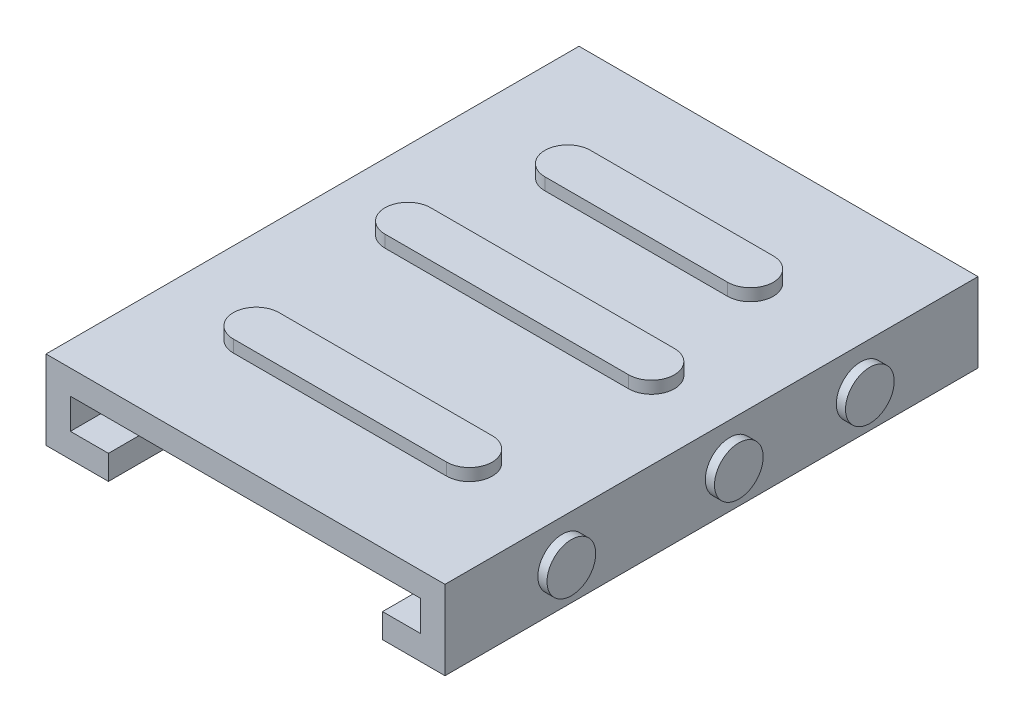
SolidWorks part; units mm, degrees
ref_plane "Front Plane" through (0, 0, 0) normal (0, 0, 1) x (1, 0, 0)
ref_plane "Top Plane" through (0, 0, 0) normal (0, 1, 0) x (1, 0, 0)
ref_plane "Right Plane" through (0, 0, 0) normal (1, 0, 0) x (0, 0, -1)
sketch "Sketch1" plane through (0, 0, 0) normal (0, 0, 1) x (1, 0, 0)
  line L0 (-59.6407, 7.2612) -> (-41.6407, 7.2612)
  line L30 (-62.1407, 7.2612) -> (-39.1407, 7.2612)
  line L34 (-62.1407, 7.2612) -> (-62.1407, 9.2612)
  line L36 (-62.1407, 9.2612) -> (-39.1407, 9.2612)
  line L37 (-39.1407, 7.2612) -> (-39.1407, 9.2612)
  line L38 (-50.6407, 9.2612) -> (-50.6407, 4.8275) construction
  line L39 (-59.6407, 7.2612) -> (-59.6407, 5.6612)
  line L40 (-59.6407, 5.6612) -> (-63.7407, 5.6612)
  line L41 (-63.7407, 5.6612) -> (-63.7407, 10.8612)
  line L42 (-63.7407, 10.8612) -> (-37.5407, 10.8612)
  line L43 (-37.5407, 10.8612) -> (-37.5407, 5.6612)
  line L44 (-37.5407, 5.6612) -> (-41.6407, 5.6612)
  line L45 (-41.6407, 5.6612) -> (-41.6407, 7.2612)
  dimension "D1" = 2
  dimension "D2" = 2.5
  dimension "D3" = 2.5
  dimension "D4" = 1.6
  dimension "D5" = 1.6
  dimension "D6" = 1.6
  dimension "D7" = 1.6
extrude "Boss-Extrude1" add sketch "Sketch1" along normal blind 35 contours L45 L44 L43 L42 L41 L40 L39 L30 L34 L36 L37
sketch "Sketch2" plane through (0, 10.8612, 0) normal (0, 1, 0) x (1, 0, 0)
  line L0 (-50.6407, 0) -> (-50.6407, -35) construction
  line L1 (-63.7407, 0) -> (-37.5407, 0) construction
  line L2 (-63.7407, -35) -> (-37.5407, -35) construction
  line L3 (-58.6263, -16.3536) -> (-42.6263, -16.3536) construction
  line L4 (-58.6263, -14.8536) -> (-42.6263, -14.8536)
  line L5 (-58.6263, -17.8536) -> (-42.6263, -17.8536)
  line L6 (-56.6407, -7.843) -> (-44.6407, -7.843) construction
  line L7 (-56.6407, -6.343) -> (-44.6407, -6.343)
  line L8 (-56.6407, -9.343) -> (-44.6407, -9.343)
  line L9 (-57.6407, -27.2963) -> (-43.6407, -27.2963) construction
  line L10 (-57.6407, -25.7963) -> (-43.6407, -25.7963)
  line L11 (-57.6407, -28.7963) -> (-43.6407, -28.7963)
  arc A0 (-58.6263, -14.8536) -> (-58.6263, -17.8536) centre (-58.6263, -16.3536) ccw
  arc A1 (-42.6263, -17.8536) -> (-42.6263, -14.8536) centre (-42.6263, -16.3536) ccw
  arc A2 (-56.6407, -6.343) -> (-56.6407, -9.343) centre (-56.6407, -7.843) ccw
  arc A3 (-44.6407, -9.343) -> (-44.6407, -6.343) centre (-44.6407, -7.843) ccw
  arc A4 (-57.6407, -25.7963) -> (-57.6407, -28.7963) centre (-57.6407, -27.2963) ccw
  arc A5 (-43.6407, -28.7963) -> (-43.6407, -25.7963) centre (-43.6407, -27.2963) ccw
  point P8 (-50.6263, -16.3536)
  point P13 (-50.6407, -7.843)
  point P20 (-50.6407, -27.2963)
  point P27 (0, 0)
  point P28 (0, 0)
extrude "Boss-Extrude2" add sketch "Sketch2" along normal blind 0.8 contours L8 A3 L7 A2 | L5 A1 L4 A0 | L11 A5 L10 A4
sketch "Sketch3" plane through (-63.7407, 0, 0) normal (-1, 0, 0) x (0, 0, 1)
  line L0 (0, 8.2612) -> (35, 8.2612) construction
  line L1 (0, 5.6612) -> (0, 10.8612) construction
  line L2 (35, 5.6612) -> (35, 10.8612) construction
  circle A0 centre (7.5265, 8.2612) radius 1.5
  circle A1 centre (16.4955, 8.2612) radius 1.5
  circle A2 centre (27.2583, 8.2612) radius 1.5
extrude "Boss-Extrude3" add sketch "Sketch3" along normal blind 0.6
sketch "Sketch5" plane through (-37.5407, 0, 0) normal (1, 0, 0) x (0, 0, -1)
  line L0 (-35, 10.8612) -> (-35, 5.6612) construction
  line L1 (0, 8.2612) -> (-35, 8.2612)
  line L2 (0, 10.8612) -> (0, 5.6612) construction
  circle A0 centre (-27.3017, 8.2612) radius 1.6
  circle A1 centre (-16.3052, 8.2612) radius 1.6
  circle A2 centre (-7.7015, 8.2612) radius 1.6
extrude "Boss-Extrude4" add sketch "Sketch5" along normal blind 0.6 contours A2 | A1 | A0
sketch "Sketch6" plane through (0, 5.6612, 0) normal (0, -1, 0) x (1, 0, 0)
  line L0 (-40.3801, 24.2088) -> (-38.3837, 24.2088)
  line L1 (-62.7119, 24.557) -> (-60.7155, 24.557)
  line L2 (-62.7119, 24.557) -> (-62.7119, 23.2106)
  line L3 (-62.7119, 23.2106) -> (-60.7155, 23.2106)
  line L4 (-60.7155, 24.557) -> (-60.7155, 23.2106)
  line L5 (-62.7119, 19.6821) -> (-60.7155, 19.6821)
  line L6 (-62.7119, 19.6821) -> (-62.7119, 18.3357)
  line L7 (-62.7119, 18.3357) -> (-60.7155, 18.3357)
  line L8 (-60.7155, 19.6821) -> (-60.7155, 18.3357)
  line L9 (-62.7119, 14.2501) -> (-60.7155, 14.2501)
  line L10 (-62.7119, 14.2501) -> (-62.7119, 12.9036)
  line L11 (-62.7119, 12.9036) -> (-60.7155, 12.9036)
  line L12 (-60.7155, 14.2501) -> (-60.7155, 12.9036)
  line L13 (-62.7119, 10.2573) -> (-60.6691, 10.2573)
  line L14 (-62.7119, 10.2573) -> (-62.7119, 8.9108)
  line L15 (-62.7119, 8.9108) -> (-60.6691, 8.9108)
  line L16 (-60.6691, 10.2573) -> (-60.6691, 8.9108)
  line L17 (-40.3801, 24.2088) -> (-40.3801, 22.8624)
  line L18 (-40.3801, 22.8624) -> (-38.3837, 22.8624)
  line L19 (-38.3837, 24.2088) -> (-38.3837, 22.8624)
  line L20 (-40.3801, 19.3339) -> (-38.3837, 19.3339)
  line L21 (-40.3801, 19.3339) -> (-40.3801, 17.9875)
  line L22 (-40.3801, 17.9875) -> (-38.3837, 17.9875)
  line L23 (-38.3837, 19.3339) -> (-38.3837, 17.9875)
  line L24 (-40.3801, 13.9018) -> (-38.3837, 13.9018)
  line L25 (-40.3801, 13.9018) -> (-40.3801, 12.5554)
  line L26 (-40.3801, 12.5554) -> (-38.3837, 12.5554)
  line L27 (-38.3837, 13.9018) -> (-38.3837, 12.5554)
  line L28 (-40.3801, 9.909) -> (-38.3373, 9.909)
  line L29 (-40.3801, 9.909) -> (-40.3801, 8.5626)
  line L30 (-40.3801, 8.5626) -> (-38.3373, 8.5626)
  line L31 (-38.3373, 9.909) -> (-38.3373, 8.5626)
  point P16 (-60.6691, 8.9108)
extrude "Boss-Extrude5" add sketch "Sketch6" along normal blind 0.6
